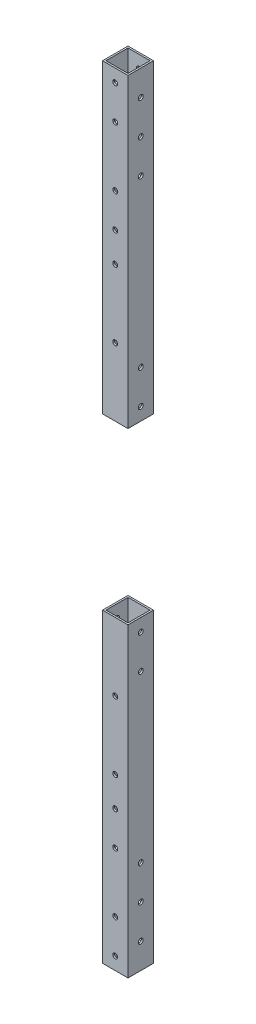
SolidWorks part; units mm, degrees
material "Thornel Mat VMA"
ref_plane "前视基准面" through (0, 0, 0) normal (0, 0, 1) x (1, 0, 0)
ref_plane "上视基准面" through (0, 0, 0) normal (0, 1, 0) x (1, 0, 0)
ref_plane "右视基准面" through (0, 0, 0) normal (1, 0, 0) x (0, 0, -1)
sketch "草图1" plane through (0, 0, 0) normal (0, 1, 0) x (1, 0, 0)
  line L1 (-7.5, -7.5) -> (7.5, -7.5)
  line L2 (-7.5, -7.5) -> (-7.5, 7.5)
  line L3 (-7.5, 7.5) -> (7.5, 7.5)
  line L4 (7.5, -7.5) -> (7.5, 7.5)
  line L5 (-7.5, -7.5) -> (7.5, 7.5) construction
  line L6 (-7.5, 7.5) -> (7.5, -7.5) construction
  point P0 (0, 0)
  dimension "D1" = 15
  dimension "D2" = 15
extrude "拉伸-薄壁1" add sketch "草图1" along normal blind 460 thin thin type one direction reverse wall 1
sketch "草图2" plane through (0, 0, 7.5) normal (0, 0, 1) x (1, 0, 0)
  line L0 (0, 0) -> (0, 460) construction
  line L1 (-7.5, 460) -> (7.5, 460) construction
  line L2 (-1000, 230) -> (49000, 230) construction
  line L3 (-7.5, 0) -> (7.5, 0) construction
  circle A0 centre (0, 7.5) radius 1.45
  circle A1 centre (0, 27.5) radius 1.45
  circle A2 centre (0, 432.5) radius 1.45
  circle A3 centre (0, 452.5) radius 1.45
  circle A4 centre (0, 62.5) radius 1.45
  circle A5 centre (0, 82.5) radius 1.45
  circle A6 centre (0, 377.5) radius 1.45
  circle A7 centre (0, 397.5) radius 1.45
  circle A8 centre (0, 140) radius 1.45
  circle A9 centre (0, 100) radius 1.45
  circle A10 centre (0, 360) radius 1.45
  circle A11 centre (0, 320) radius 1.45
  point P8 (0, 230)
  dimension "D1" = 2.9
  dimension "D4" = 35
  dimension "D6" = 40
  dimension "D2" = 7.5
  dimension "D3" = 20
  dimension "D5" = 20
  dimension "D7" = 90
extrude "切除-拉伸1" cut sketch "草图2" against normal through all
sketch "草图3" plane through (7.5, 0, 0) normal (1, 0, 0) x (0, 0, -1)
  line L0 (0, 0) -> (0, 460) construction
  line L1 (-7.5, 460) -> (7.5, 460) construction
  line L2 (-1000, 230) -> (49000, 230) construction
  line L3 (-7.5, 0) -> (7.5, 0) construction
  circle A0 centre (0, 15) radius 1.45
  circle A1 centre (0, 35) radius 1.45
  circle A2 centre (0, 425) radius 1.45
  circle A3 centre (0, 445) radius 1.45
  circle A4 centre (0, 172.5) radius 1.45
  circle A5 centre (0, 192.5) radius 1.45
  circle A6 centre (0, 152.5) radius 1.45
  circle A7 centre (0, 307.5) radius 1.45
  circle A8 centre (0, 267.5) radius 1.45
  circle A9 centre (0, 287.5) radius 1.45
  circle A10 centre (0, 55) radius 1.45
  circle A11 centre (0, 405) radius 1.45
  point P12 (0, 230)
  dimension "D3" = 2.9
  dimension "D4" = 2.9
  dimension "D5" = 20
  dimension "D6" = 20
  dimension "D7" = 115
  dimension "D8" = 20
  dimension "D1" = 15
  dimension "D2" = 20
extrude "切除-拉伸2" cut sketch "草图3" against normal through all
sketch "草图4" plane through (7.5, 0, 0) normal (1, 0, 0) x (0, 0, -1)
  line L0 (-7.5, 460) -> (-7.5, 0) construction
  line L1 (-7.5, 280) -> (7.5, 280)
  line L2 (-7.5, 280) -> (-7.5, 180)
  line L3 (-7.5, 180) -> (7.5, 180)
  line L4 (7.5, 280) -> (7.5, 180)
  line L5 (7.5, 460) -> (7.5, 0) construction
  circle A0 centre (0, 172.5) radius 1.45 construction
  circle A1 centre (0, 287.5) radius 1.45 construction
  dimension "D1" = 7.5
  dimension "D2" = 7.5
extrude "切除-拉伸3" cut sketch "草图4" against normal through all
